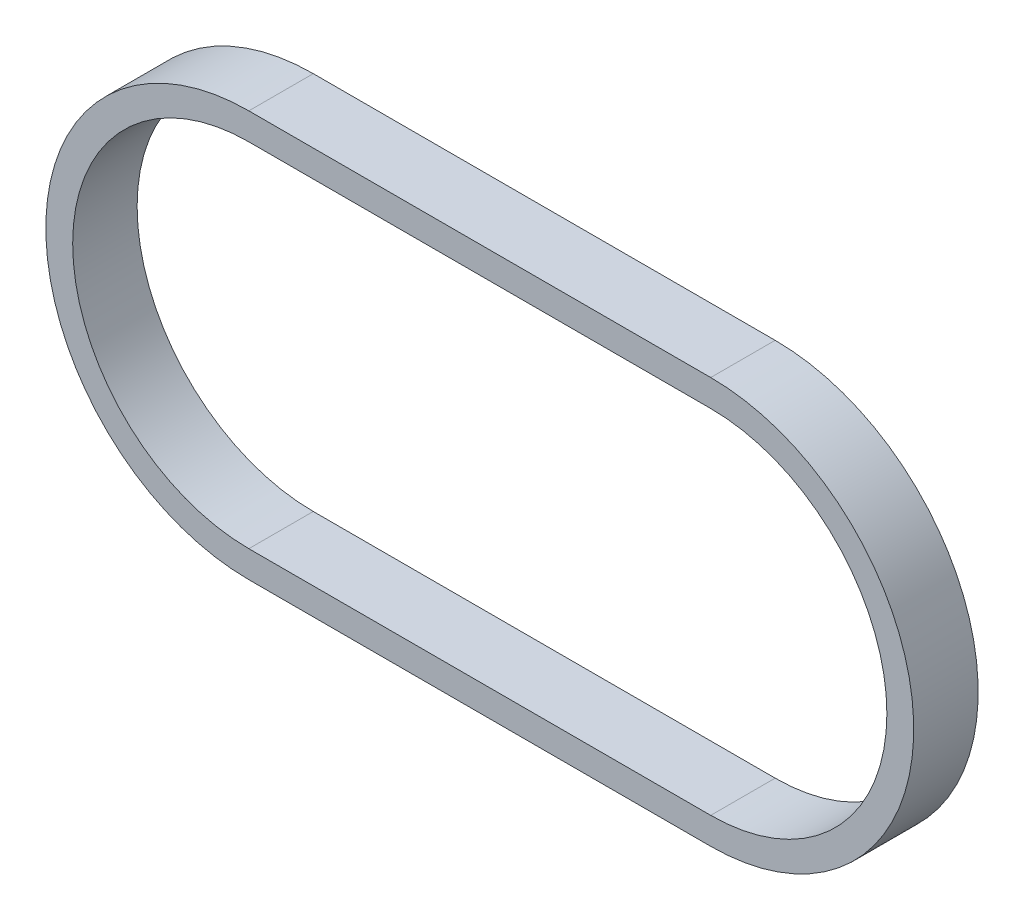
SolidWorks part; units mm, degrees
ref_plane "Plan de face" through (0, 0, 0) normal (0, 0, 1) x (1, 0, 0)
ref_plane "Plan de dessus" through (0, 0, 0) normal (0, 1, 0) x (1, 0, 0)
ref_plane "Plan de droite" through (0, 0, 0) normal (1, 0, 0) x (0, 0, -1)
sketch "Esquisse4" plane through (0, 0, 0) normal (0, 0, 1) x (1, 0, 0)
  line L0 (-21.5, -18.9) -> (21.5, -18.9)
  line L2 (21.5, -16.4) -> (-21.5, -16.4)
  line L4 (21.5, 18.9) -> (-21.5, 18.9)
  line L5 (-21.5, 16.4) -> (21.5, 16.4)
  arc A0 (21.5, -18.9) -> (21.5, 18.9) centre (21.5, 0) ccw
  arc A1 (21.5, 16.4) -> (21.5, -16.4) centre (21.5, 0) cw
  arc A2 (-21.5, -16.4) -> (-21.5, 16.4) centre (-21.5, 0) cw
  arc A3 (-21.5, 18.9) -> (-21.5, -18.9) centre (-21.5, 0) ccw
  point P8 (0, 0)
  point P9 (0, 0)
  point P10 (0, 0)
  point P18 (0, 0)
  dimension "D1" = 2.5
  dimension "D2" = 37.8
  dimension "D3" = 18.9
  dimension "D4" = 43
  dimension "D5" = 21.5
extrude "Boss.-Extru.2" add sketch "Esquisse4" along normal blind 6
